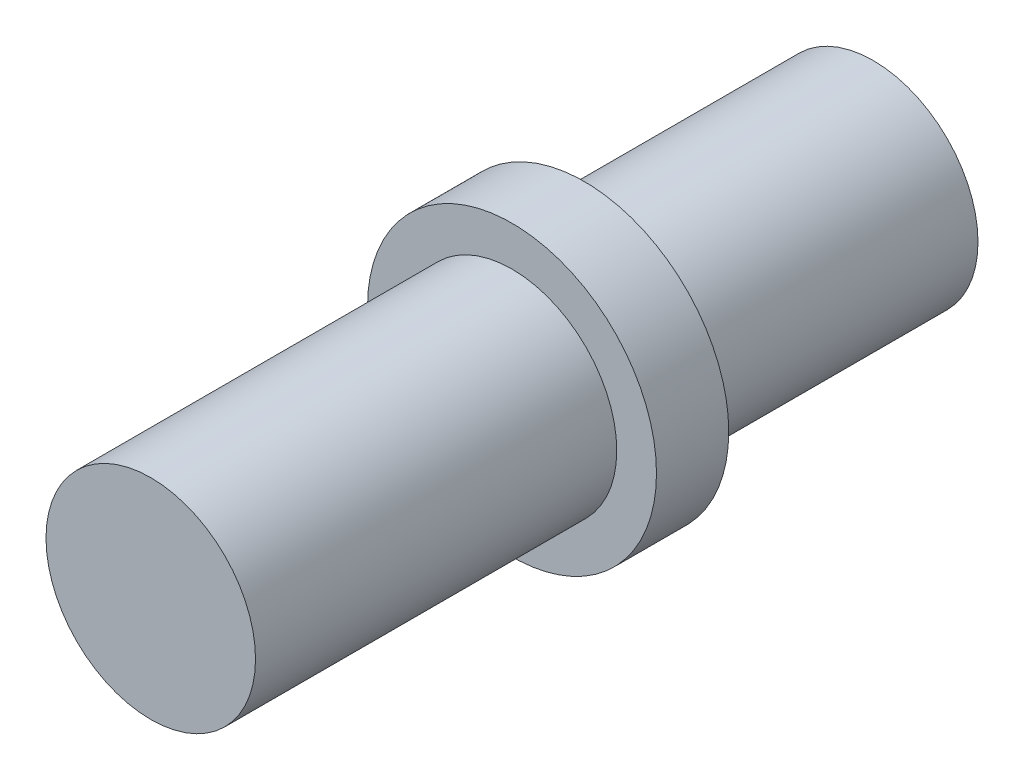
SolidWorks part; units mm, degrees
ref_plane "Front Plane" through (0, 0, 0) normal (0, 0, 1) x (1, 0, 0)
ref_plane "Top Plane" through (0, 0, 0) normal (0, 1, 0) x (1, 0, 0)
ref_plane "Right Plane" through (0, 0, 0) normal (1, 0, 0) x (0, 0, -1)
other "Configuration Table"
sketch "Sketch2" plane through (0, 0, 0) normal (0, 0, 1) x (1, 0, 0)
  circle A0 centre (0, 0) radius 2.9
extrude "Locator_shaft" add sketch "Sketch2" along normal blind 20 from offset 0
sketch "Sketch3" plane through (0, 0, 0) normal (0, 0, 1) x (1, 0, 0)
  circle A0 centre (0, 0) radius 4
extrude "Locator_shoulder" add sketch "Sketch3" along normal blind 2 from offset 8
